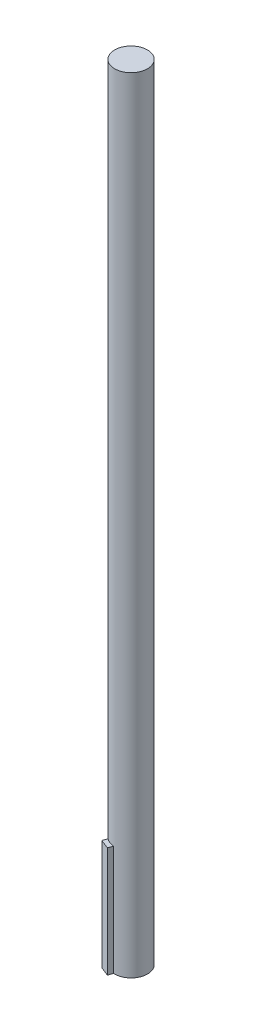
SolidWorks part; units mm, degrees
material "1023 Carbon Steel Sheet (SS)"
ref_plane "Front Plane" through (0, 0, 0) normal (0, 0, 1) x (1, 0, 0)
ref_plane "Top Plane" through (0, 0, 0) normal (0, 1, 0) x (1, 0, 0)
ref_plane "Right Plane" through (0, 0, 0) normal (1, 0, 0) x (0, 0, -1)
sketch "Sketch2" plane through (0, 0, 0) normal (0, 1, 0) x (1, 0, 0)
  line L0 (-0.8327, -13.3426) -> (-2.265, -17.0774)
  line L1 (-2.265, -17.0774) -> (-9.7346, -14.2129)
  line L2 (-9.7346, -14.2129) -> (-8.3023, -10.4781)
  arc A0 (-0.8327, -13.3426) -> (-8.3023, -10.4781) centre (0, 0) ccw
extrude "Boss-Extrude1" add sketch "Sketch2" along normal blind 90
sketch "Sketch3" plane through (0, 90, 0) normal (0, 1, 0) x (1, 0, 0)
  circle A0 centre (0, 0) radius 13.3686
extrude "Boss-Extrude2" add sketch "Sketch3" along normal blind 550
